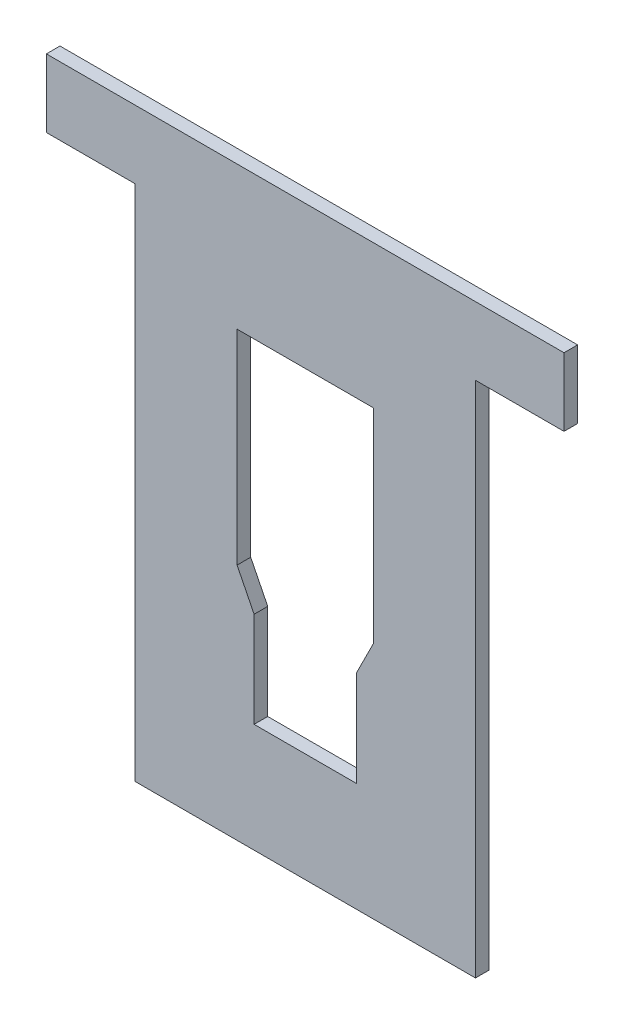
SolidWorks part; units mm, degrees
material "AISI 316 Stainless Steel Sheet (SS)"
ref_plane "Front Plane" through (0, 0, 0) normal (0, 0, 1) x (1, 0, 0)
ref_plane "Top Plane" through (0, 0, 0) normal (0, 1, 0) x (1, 0, 0)
ref_plane "Right Plane" through (0, 0, 0) normal (1, 0, 0) x (0, 0, -1)
sketch "Sketch1" plane through (0, 0, 0) normal (0, 0, 1) x (1, 0, 0)
  line L0 (0, 0) -> (12.7, 0)
  line L1 (10.6172, 0) -> (-10.6172, 0) construction
  line L2 (12.7, 0) -> (12.7, 19.304)
  line L3 (12.7, 19.304) -> (16.002, 19.304)
  line L4 (16.002, 19.304) -> (16.002, 21.844)
  line L5 (16.002, 21.844) -> (-3.302, 21.844)
  line L6 (-3.302, 21.844) -> (-3.302, 19.304)
  line L7 (-3.302, 19.304) -> (0, 19.304)
  line L8 (0, -12.0142) -> (0, 12.0142) construction
  line L9 (0, 19.304) -> (0, 0)
  line L10 (3.81, 16.51) -> (8.89, 16.51)
  line L11 (8.89, 16.51) -> (8.89, 8.89)
  line L12 (8.89, 8.89) -> (8.255, 7.62)
  line L13 (8.255, 7.62) -> (8.255, 4.064)
  line L14 (8.255, 4.064) -> (4.445, 4.064)
  line L15 (4.445, 4.064) -> (4.445, 7.62)
  line L16 (4.445, 7.62) -> (3.81, 8.89)
  line L17 (3.81, 8.89) -> (3.81, 16.51)
  point P15 (6.35, 21.844)
  point P22 (6.35, 0)
  point P23 (6.35, 16.51)
  point P24 (6.35, 4.064)
  dimension "D1" = 12.7
  dimension "D2" = 19.304
  dimension "D3" = 21.844
  dimension "D4" = 2.54
  dimension "D5" = 12.446
  dimension "D6" = 5.08
  dimension "D7" = 3.81
  dimension "D8" = 4.064
  dimension "D9" = 3.556
  dimension "D10" = 7.62
extrude "Boss-Extrude1" add sketch "Sketch1" along normal blind 0.508
